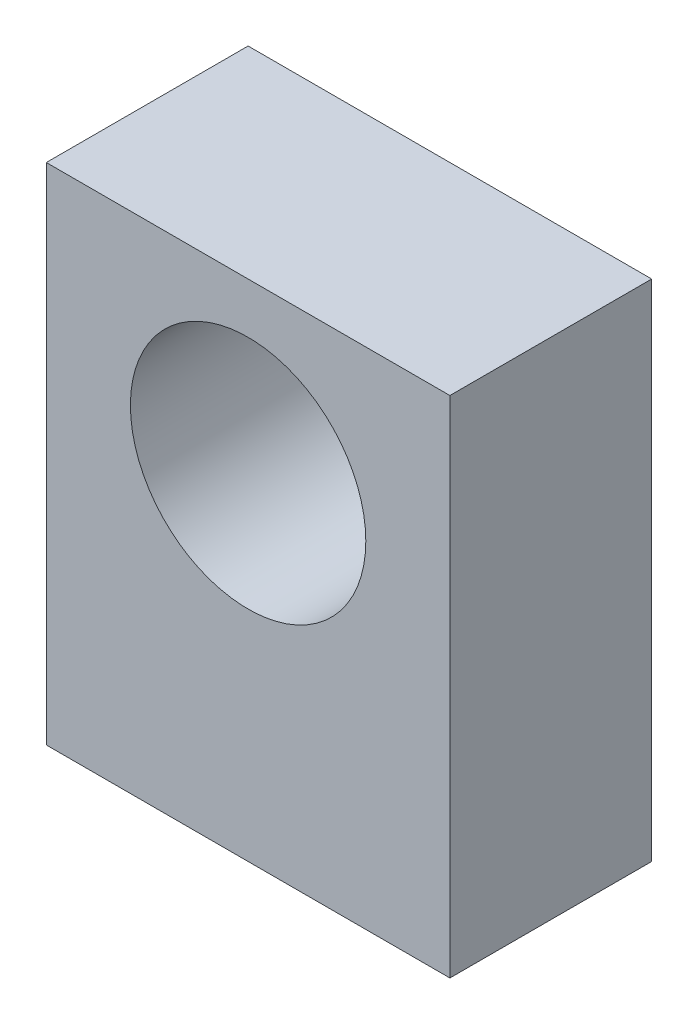
SolidWorks part; units mm, degrees
ref_plane "Front Plane" through (0, 0, 0) normal (0, 0, 1) x (1, 0, 0)
ref_plane "Top Plane" through (0, 0, 0) normal (0, 1, 0) x (1, 0, 0)
ref_plane "Right Plane" through (0, 0, 0) normal (1, 0, 0) x (0, 0, -1)
sketch "Sketch2" plane through (0, 0, 0) normal (0, 0, 1) x (1, 0, 0)
  line L0 (-69.75, 52.75) -> (-69.75, 42.75)
  line L2 (-69.75, 52.75) -> (-63.75, 52.75)
  line L3 (-69.75, 52.75) -> (-69.75, 50.25)
  line L4 (-69.75, 50.25) -> (-63.75, 50.25)
  line L5 (-63.75, 52.75) -> (-63.75, 50.25)
  line L7 (-63.75, 42.75) -> (-69.75, 42.75)
  line L8 (-63.75, 42.75) -> (-63.75, 52.75)
  line L9 (-63.75, 52.75) -> (-69.75, 52.75)
  line L11 (-63.75, 42.75) -> (-69.75, 52.75) construction
  line L12 (-63.75, 52.75) -> (-69.75, 42.75) construction
  circle A1 centre (-66.75, 47.75) radius 1.75
  point P2 (-65.7383, 47.75)
  point P12 (-66.75, 47.75)
  line M9 (-62.75, 50.25) -> (-69.25, 50.25)
  line M10 (-69.25, 50.25) -> (-69.25, -50.25)
  circle M12 centre (-66.75, 47.75) radius 1.5
  dimension "D4" = 3.5
  dimension "D1" = 6
  dimension "D2" = 10
  dimension "D3" = 2.5
extrude "Boss-Extrude1" add sketch "Sketch2" along normal blind 3 contours L7 L8 M9 M10 M12 | L7 L4 L0 M10
